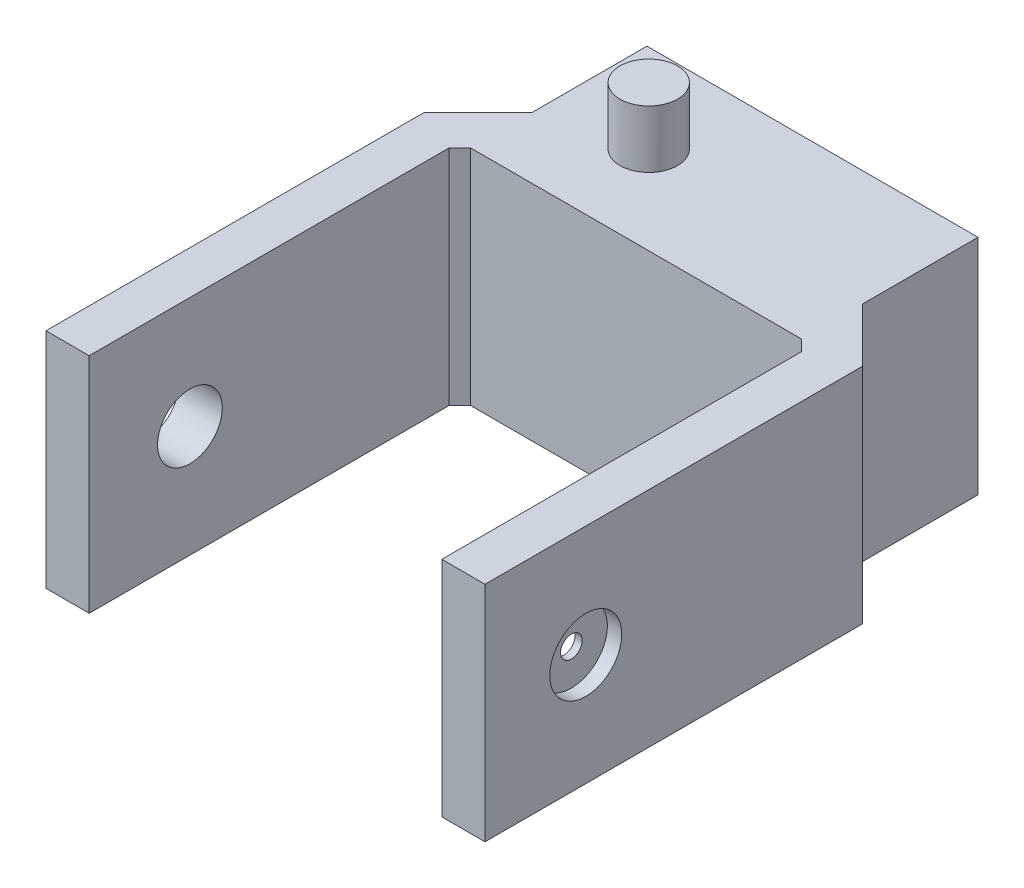
SolidWorks part; units mm, degrees
material "ABS"
ref_plane "Front Plane" through (0, 0, 0) normal (0, 0, 1) x (1, 0, 0)
ref_plane "Top Plane" through (0, 0, 0) normal (0, 1, 0) x (1, 0, 0)
ref_plane "Right Plane" through (0, 0, 0) normal (1, 0, 0) x (0, 0, -1)
sketch "Sketch1" plane through (0, 0, 0) normal (0, 1, 0) x (1, 0, 0)
  line L1 (-23, -12.25) -> (23, -12.25)
  line L2 (-23, -12.25) -> (-23, 12.25)
  line L3 (-23, 12.25) -> (23, 12.25)
  line L4 (23, -12.25) -> (23, 12.25)
  line L5 (-23, -12.25) -> (23, 12.25) construction
  line L6 (-23, 12.25) -> (23, -12.25) construction
  point P0 (0, 0)
  dimension "D1" = 24.5
  dimension "D2" = 46
extrude "Body" add sketch "Sketch1" along normal blind 31
sketch "Sketch3" plane through (0, 0, 0) normal (0, 1, 0) x (1, 0, 0)
  line L0 (-23, -12.25) -> (23, -12.25) construction
  line L1 (-21, 10.25) -> (21, 10.25)
  line L2 (-21, 10.25) -> (-21, -10.25)
  line L3 (-21, -10.25) -> (21, -10.25)
  line L4 (21, 10.25) -> (21, -10.25)
  line L5 (-21, 10.25) -> (21, -10.25) construction
  line L6 (-21, -10.25) -> (21, 10.25) construction
  line L7 (23, -12.25) -> (23, 12.25) construction
  point P0 (0, 0)
  dimension "D1" = 2
  dimension "D2" = 2
extrude "Servo Hole" cut sketch "Sketch3" along normal blind 29
sketch "Sketch6" plane through (0, 31, 0) normal (0, 1, 0) x (1, 0, 0)
  line L0 (23, -12.25) -> (23, 12.25) construction
  line L2 (10.5, 0) -> (0, 0) construction
  circle A0 centre (10.5, 0) radius 4
  dimension "D2" = 8
  dimension "D1" = 12.5
extrude "Boss-Extrude3" add sketch "Sketch6" along normal blind 8
sketch "Sketch8" plane through (0, 0, 0) normal (0, -1, 0) x (1, 0, 0)
  line L0 (-23, 12.25) -> (-24.5, 13.75)
  line L1 (-23, 3.7647) -> (-30.5, 11.2647)
  line L2 (-23, -12.25) -> (-23, 12.25) construction
  line L3 (-30.5, 11.2647) -> (-30.5, 63.75)
  line L4 (-30.5, 63.75) -> (-24.5, 63.75)
  line L5 (-24.5, 63.75) -> (-24.5, 13.75)
  line L6 (0, 0) -> (0, 31.6845) construction
  line L7 (24.5, 63.75) -> (24.5, 13.75)
  line L8 (30.5, 63.75) -> (24.5, 63.75)
  line L9 (30.5, 11.2647) -> (30.5, 63.75)
  line L10 (23, 3.7647) -> (30.5, 11.2647)
  line L11 (23, 12.25) -> (24.5, 13.75)
  line L12 (-23, 12.25) -> (-23, 3.7647)
  line L13 (23, 12.25) -> (23, 3.7647)
  dimension "D1" = 1.5
  dimension "D2" = 1.5
  dimension "D3" = 6
  dimension "D4" = 6
  dimension "D5" = 50
  dimension "D6" = 49
extrude "Boss-Extrude4" add sketch "Sketch8" against normal up to surface (31 mm away) up to face at (10.5, 31, -4)
sketch "Sketch5" plane through (23, 0, 0) normal (-1, 0, 0) x (0, 0, 1)
  line L8 (-6, 27) -> (6, 27)
  line L13 (6, 27) -> (6, 22)
  line L14 (6, 22) -> (4.25, 22)
  line L17 (4.25, 22) -> (4.25, 2)
  line L18 (4.25, 2) -> (-4.25, 2)
  line L19 (3.7647, 0) -> (-12.25, 0) construction
  line L21 (-4.25, 2) -> (-4.25, 22)
  line L22 (-4.25, 22) -> (-6, 22)
  line L23 (-6, 22) -> (-6, 27)
  line L25 (-12.25, 31) -> (3.7647, 31) construction
  dimension "D1" = 4
  dimension "D2" = 2
  dimension "D3" = 5
  dimension "D4" = 12
  dimension "D5" = 5
  dimension "D6" = 1.75
  dimension "D7" = 1.75
  dimension "D8" = 4.25
extrude "Cut-Extrude3" cut sketch "Sketch5" against normal blind 29 and the other way blind 2
sketch "Sketch10" plane through (-24.5, 0, 0) normal (1, 0, 0) x (0, 0, -1)
  line L0 (-63.75, 31) -> (-63.75, 0) construction
  line L3 (-32.75, 12.5) -> (-49.75, 9)
  line L5 (-49.75, 22) -> (-32.75, 18.5)
  line L6 (-63.75, 31) -> (-13.75, 31) construction
  arc A1 (-49.75, 22) -> (-49.75, 9) centre (-49.75, 15.5) ccw
  arc A3 (-32.75, 18.5) -> (-32.75, 12.5) centre (-32.75, 15.5) cw
  dimension "D2" = 15.5
  dimension "D1" = 14
  dimension "D3" = 17
  dimension "D4" = 6.5
  dimension "D5" = 3
extrude "Cut-Extrude4" cut sketch "Sketch10" against normal blind 3
sketch "Sketch11" plane through (-24.5, 0, 0) normal (1, 0, 0) x (0, 0, -1)
  circle A0 centre (-49.75, 15.5) radius 1.5
  dimension "D1" = 3
extrude "Cut-Extrude5" cut sketch "Sketch11" against normal through all both and the other way through all
sketch "Sketch12" plane through (30.5, 0, 0) normal (1, 0, 0) x (0, 0, -1)
  circle A0 centre (-49.75, 15.5) radius 4.5
  dimension "D1" = 9
extrude "Cut-Extrude6" cut sketch "Sketch12" against normal blind 6
sketch "Sketch13" plane through (-30.5, 0, 0) normal (-1, 0, 0) x (0, 0, 1)
  circle A0 centre (49.75, 15.5) radius 5
  dimension "D1" = 10
extrude "Cut-Extrude7" cut sketch "Sketch13" against normal blind 2 contours A0
mirror "Mirror2" about plane through (-30.5, 91.4523, 11.2647) normal (-1, 0, 0) of bodies 111
delete or keep bodies "Body-Delete/Keep 2" type keep bodies bodies 116
